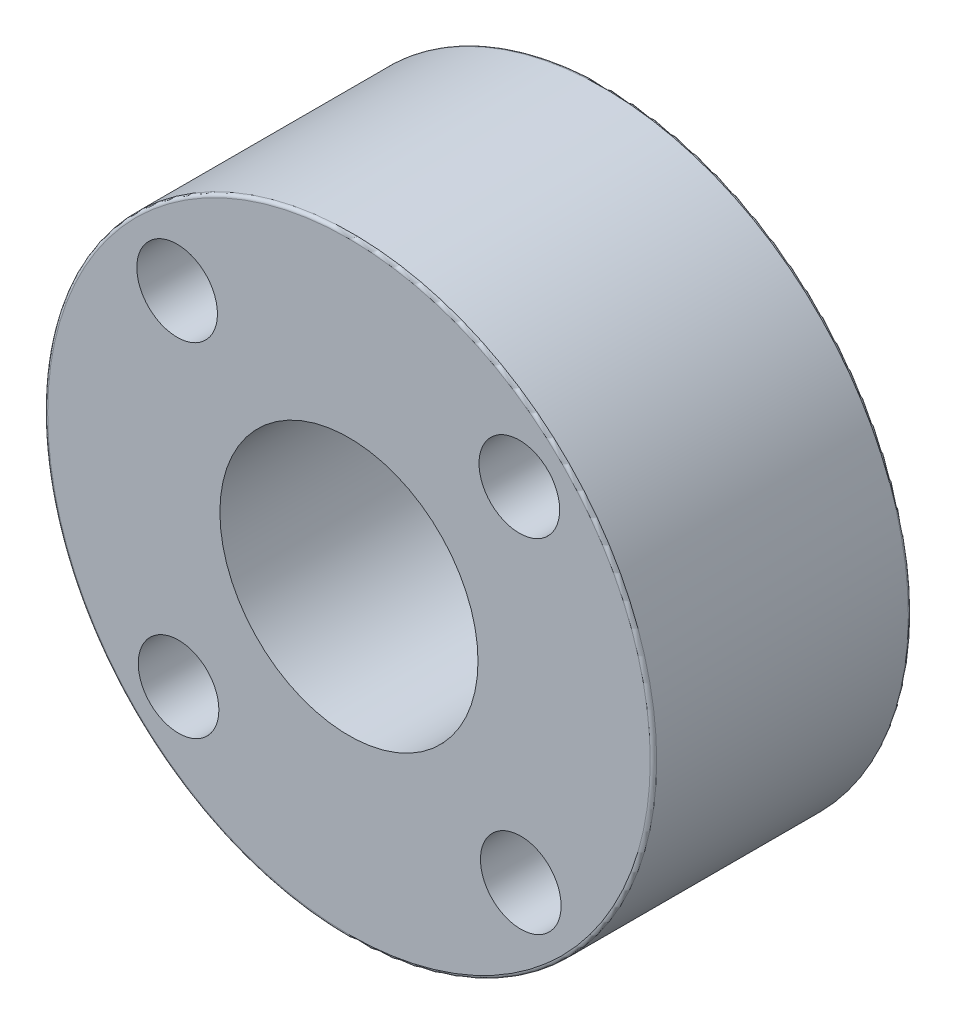
SolidWorks part; units mm, degrees
material "3.3549 (EN-AW 5182)"
ref_plane "Спереди" through (0, 0, 0) normal (0, 0, 1) x (1, 0, 0)
ref_plane "Сверху" through (0, 0, 0) normal (0, 1, 0) x (1, 0, 0)
ref_plane "Справа" through (0, 0, 0) normal (1, 0, 0) x (0, 0, -1)
sketch "Эскиз1" plane through (0, 0, 0) normal (0, 0, 1) x (1, 0, 0)
  circle A0 centre (0, 0) radius 9.4381
  circle A1 centre (0, 0) radius 4
  circle A2 centre (-5.3252, 5.2813) radius 1.25
  circle A3 centre (-5.2813, -5.3252) radius 1.25
  circle A4 centre (5.3252, -5.2813) radius 1.25
  circle A5 centre (5.2813, 5.3252) radius 1.25
extrude "Бобышка-Вытянуть1" add sketch "Эскиз1" along normal blind 8
fillet "Скругление1" radius 0.1 2 edges at (9.4381, 0, 0) (9.4381, 0, 8)
